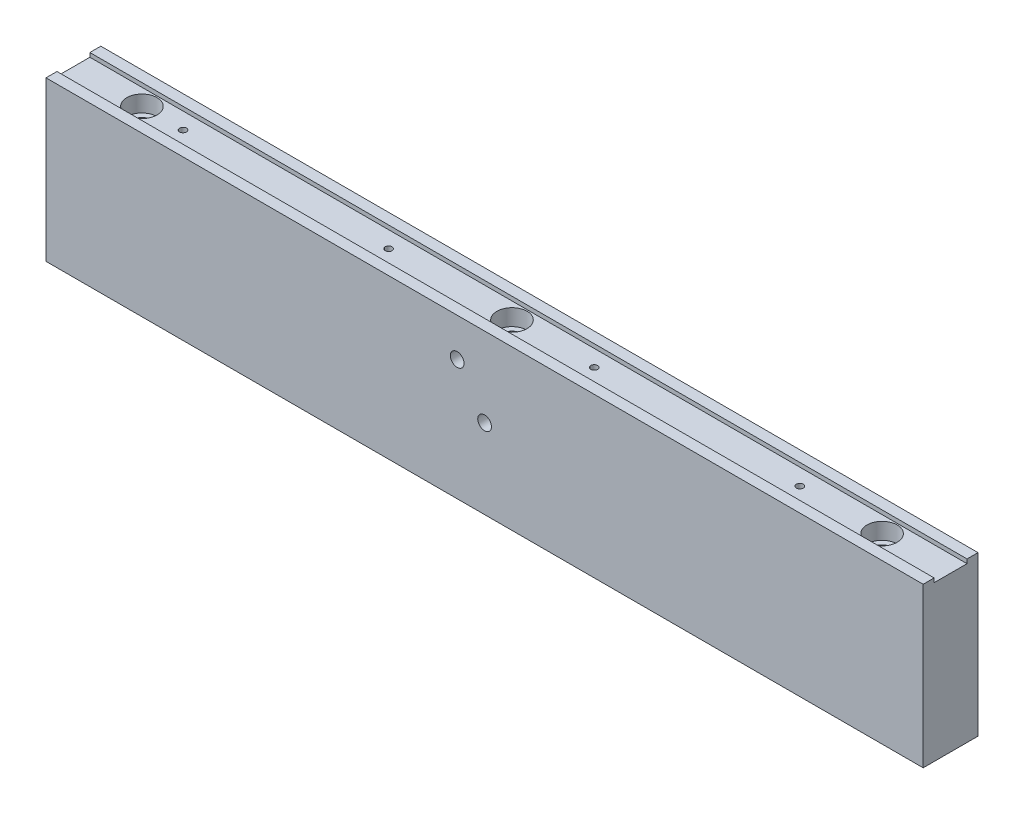
SolidWorks part; units mm, degrees
material "SKD11淬火HRC56-60"
ref_plane "前基準面" through (0, 0, 0) normal (0, 0, 1) x (1, 0, 0)
ref_plane "上基準面" through (0, 0, 0) normal (0, 1, 0) x (1, 0, 0)
ref_plane "右基準面" through (0, 0, 0) normal (1, 0, 0) x (0, 0, -1)
sketch "草图1" plane through (0, 0, 0) normal (0, 0, 1) x (1, 0, 0)
  line L1 (0, 0) -> (320, 0)
  line L2 (0, 0) -> (0, 58)
  line L3 (0, 58) -> (320, 58)
  line L4 (320, 0) -> (320, 58)
  dimension "D1" = 320
  dimension "D2" = 58
extrude "凸台-拉伸1" add sketch "草图1" along normal blind 20
sketch "草图2" plane through (0, 0, 0) normal (-1, 0, 0) x (0, 0, 1)
  line L0 (20, 58) -> (0, 58) construction
  line L1 (4, 58) -> (16, 58)
  line L2 (4, 58) -> (4, 56.5)
  line L3 (4, 56.5) -> (16, 56.5)
  line L4 (16, 58) -> (16, 56.5)
  line L5 (10, 58) -> (10, 49.2188) construction
  dimension "D1" = 12
  dimension "D2" = 1.5
extrude "切除-拉伸1" cut sketch "草图2" against normal through all
hole_wizard "M6 螺纹孔1" positions "草图4" profile "草图3" tap size "M6" standard "ISO"
sketch "草图4" plane through (0, 0, 20) normal (0, 0, 1) x (1, 0, 0)
  line L0 (160, 0) -> (160, 58) construction
  line L1 (0, 0) -> (320, 0) construction
  line L2 (320, 58) -> (0, 58) construction
  point P0 (160, 29)
  point P8 (150, 44)
  dimension "D1" = 15
  dimension "D2" = 10
sketch "草图3" plane through (160, 29, 20) normal (1, 0, 0) x (0, -1, 0)
  line L0 (0, 0) -> (0, 16.5022)
  line L1 (0, 16.5022) -> (2.5, 15)
  line L2 (2.5, 15) -> (2.5, 0)
  line L5 (2.5, 0) -> (0, 0)
  line L10 (0, 16.5022) -> (-2.5, 15) construction
  line L11 (0, -6.35) -> (0, 107.95) construction
  dimension "螺纹孔钻头直径" = 5
  dimension "螺纹孔钻头深度" = 15
  dimension "导头角度" = 118
cosmetic thread "孔螺蚊线1" parameters "D1"=12, "D2"=6
cosmetic thread "孔螺蚊线12" parameters "D1"=12, "D2"=6
hole_wizard "M6 六角凹头螺钉的柱形沉头孔1" positions "草图6" profile "草图5" counterbore size "M6" standard "ISO" end condition through all
sketch "草图6" plane through (0, 56.5, 0) normal (0, 1, 0) x (-1, 0, 0)
  line L0 (-160, 20) -> (-160, 0) construction
  line L1 (-320, 20) -> (0, 20) construction
  line L2 (-320, 0) -> (0, 0) construction
  line L3 (0, 10) -> (-320, 10) construction
  line L4 (0, 4) -> (0, 16) construction
  line L5 (-320, 4) -> (-320, 16) construction
  point P0 (-25, 10)
  point P1 (-295, 10)
  point P3 (-160, 10)
  dimension "D1" = 270
sketch "草图5" plane through (25, 56.5, 10) normal (1, 0, 0) x (0, 0, 1)
  line L0 (0, 0) -> (0, 56.5)
  line L1 (0, 56.5) -> (3.5, 56.5)
  line L3 (3.5, 56.5) -> (3.5, 6)
  line L4 (3.5, 6) -> (5.5, 6)
  line L5 (5.5, 6) -> (5.5, 0)
  line L7 (5.5, 0) -> (0, 0)
  line L11 (0, -6.35) -> (0, 107.95) construction
  dimension "通孔孔直径" = 7
  dimension "通孔孔深度" = 56.5
  dimension "柱形沉头孔直径" = 11
  dimension "柱形沉头孔深度" = 6
hole_wizard "M3 螺纹孔1" positions "草图8" profile "草图7" tap size "M3" standard "ISO"
sketch "草图8" plane through (0, 56.5, 0) normal (0, 1, 0) x (-1, 0, 0)
  point P0 (-265, 10)
  point P4 (-40, 10)
  point P7 (-190, 10)
  point P10 (-115, 10)
sketch "草图7" plane through (265, 56.5, 10) normal (1, 0, 0) x (0, 0, 1)
  line L0 (0, 0) -> (0, 8.2511)
  line L1 (0, 8.2511) -> (1.25, 7.5)
  line L2 (1.25, 7.5) -> (1.25, 0)
  line L5 (1.25, 0) -> (0, 0)
  line L10 (0, 8.2511) -> (-1.25, 7.5) construction
  line L11 (0, -6.35) -> (0, 107.95) construction
  dimension "螺纹孔钻头直径" = 2.5
  dimension "螺纹孔钻头深度" = 7.5
  dimension "导头角度" = 118
cosmetic thread "孔螺蚊线2" parameters "D1"=6, "D2"=3
cosmetic thread "孔螺蚊线3" parameters "D1"=6, "D2"=3
cosmetic thread "孔螺蚊线4" parameters "D1"=6, "D2"=3
cosmetic thread "孔螺蚊线5" parameters "D1"=6, "D2"=3
hole_wizard "M6 螺纹孔2" positions "草图10" profile "草图9" tap size "M6" standard "ISO"
sketch "草图10" plane through (0, 0, 0) normal (0, 0, -1) x (-1, 0, 0)
  line L0 (-320, 0) -> (-320, 58) construction
  point P0 (-304, 46.6215)
  point P1 (-276, 46.6215)
  dimension "D1" = 16
  dimension "D2" = 28
sketch "草图9" plane through (304, 46.6215, 0) normal (1, 0, 0) x (0, 1, 0)
  line L0 (0, 0) -> (0, 16.5022)
  line L1 (0, 16.5022) -> (2.5, 15)
  line L2 (2.5, 15) -> (2.5, 0)
  line L5 (2.5, 0) -> (0, 0)
  line L10 (0, 16.5022) -> (-2.5, 15) construction
  line L11 (0, -6.35) -> (0, 107.95) construction
  dimension "螺纹孔钻头直径" = 5
  dimension "螺纹孔钻头深度" = 15
  dimension "导头角度" = 118
cosmetic thread "孔螺蚊线6" parameters "D1"=12, "D2"=6
cosmetic thread "孔螺蚊线7" parameters "D1"=12, "D2"=6
hole_wizard "M3 螺纹孔2" positions "草图12" profile "草图11" tap size "M3" standard "ISO"
sketch "草图12" plane through (0, 0, 0) normal (0, 0, -1) x (-1, 0, 0)
  line L0 (-320, 58) -> (0, 58) construction
  line L1 (0, 58) -> (0, 0) construction
  point P0 (-10, 35.4)
  point P1 (-29.5, 35.4)
  point P3 (-244, 35.4)
  point P5 (-224.5, 35.4)
  dimension "D1" = 19.5
  dimension "D2" = 19.5
  dimension "D3" = 22.6
  dimension "D4" = 10
  dimension "D5" = 195
sketch "草图11" plane through (10, 35.4, 0) normal (1, 0, 0) x (0, 1, 0)
  line L0 (0, 0) -> (0, 8.2511)
  line L1 (0, 8.2511) -> (1.25, 7.5)
  line L2 (1.25, 7.5) -> (1.25, 0)
  line L5 (1.25, 0) -> (0, 0)
  line L10 (0, 8.2511) -> (-1.25, 7.5) construction
  line L11 (0, -6.35) -> (0, 107.95) construction
  dimension "螺纹孔钻头直径" = 2.5
  dimension "螺纹孔钻头深度" = 7.5
  dimension "导头角度" = 118
cosmetic thread "孔螺蚊线8" parameters "D1"=6, "D2"=3
cosmetic thread "孔螺蚊线9" parameters "D1"=6, "D2"=3
cosmetic thread "孔螺蚊线10" parameters "D1"=6, "D2"=3
cosmetic thread "孔螺蚊线11" parameters "D1"=6, "D2"=3
